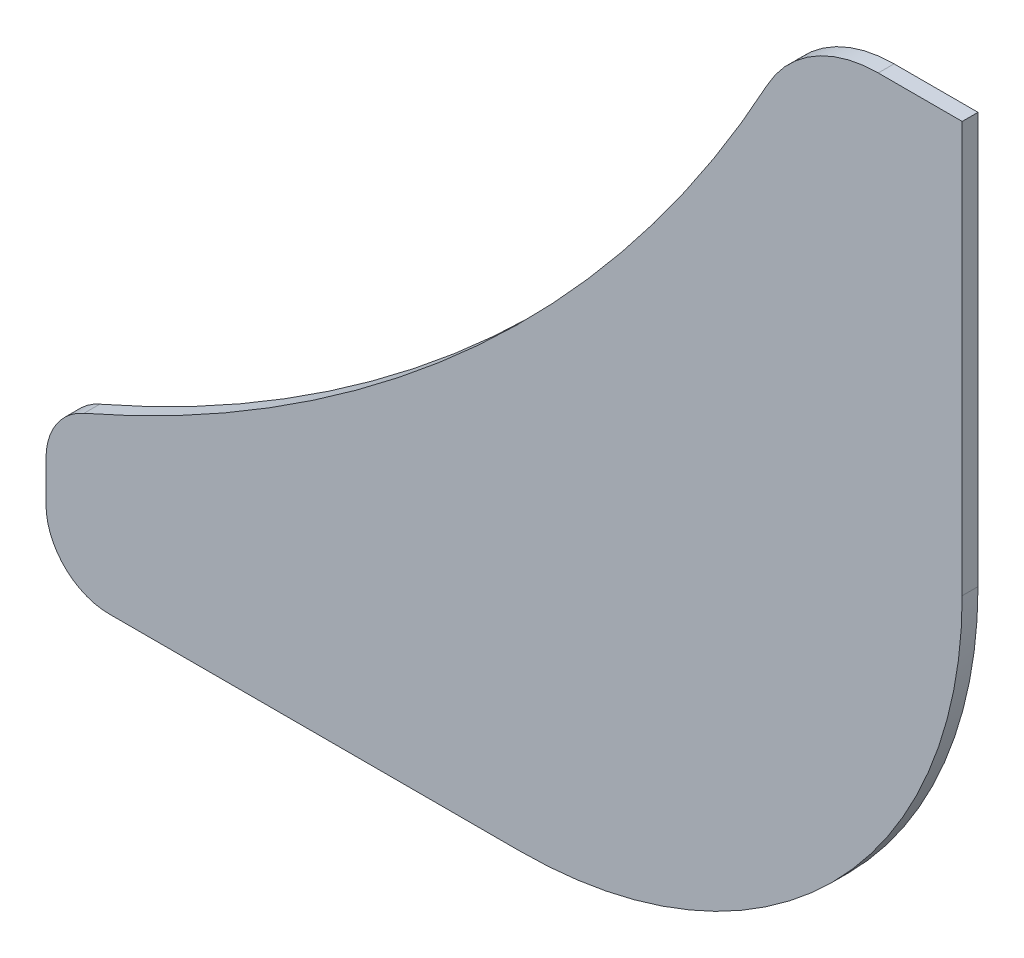
SolidWorks part; units mm, degrees
ref_plane "Front Plane" through (0, 0, 0) normal (0, 0, 1) x (1, 0, 0)
ref_plane "Top Plane" through (0, 0, 0) normal (0, 1, 0) x (1, 0, 0)
ref_plane "Right Plane" through (0, 0, 0) normal (1, 0, 0) x (0, 0, -1)
sketch "Sketch1" plane through (0, 0, 0) normal (0, 0, 1) x (1, 0, 0)
  line L15 (771.9038, 126.6023) -> (771.9038, 164.7023)
  line L17 (203.2, -228.6) -> (203.2, -261.62)
  line L20 (0, 0) -> (82.8917, 0) construction
  line L21 (0, 0) -> (0, -86.4487) construction
  line L22 (771.9038, 126.6023) -> (907.5478, 126.6023) construction
  line L25 (571.4712, -109.22) -> (571.4712, 55.88)
  line L26 (228.6, -287.02) -> (393.6712, -287.02)
  line L27 (312.4515, -206.6231) -> (466.4308, -117.7231) construction
  line L28 (451.8433, -111.2042) -> (546.0712, -26.0566) construction
  line L29 (571.4712, 55.88) -> (537.7285, 55.88)
  line L40 (361.6164, -231.6548) -> (133.988, -252.7091) construction
  line L41 (157.3315, -273.5734) -> (-70.4948, -254.7805) construction
  arc A5 (203.2, -261.62) -> (228.6, -287.02) centre (228.6, -261.62) ccw
  arc A6 (203.2, -228.6) -> (493.0974, 29.3434) centre (-9.9332, 302.8128) ccw
  arc A7 (571.4712, -109.22) -> (393.6712, -287.02) centre (393.6712, -109.22) cw
  arc A8 (537.7285, 55.88) -> (493.0974, 29.3434) centre (537.7285, 5.08) ccw
  spline S0 degree 3 poles (360.3362, -232.1476) (361.944, -231.5594) (360.2733, -231.9279) (358.8705, -232.1286) (355.491, -232.7497) (351.3118, -233.4654) (345.8288, -234.3937) (339.3319, -235.4503) (331.8137, -236.6267) (323.3898, -237.8749) (314.1481, -239.1645) (304.196, -240.4529) (293.645, -241.7102) (282.6109, -242.9031) (271.2144, -244.0118) (259.5796, -245.0173) (247.8327, -245.923) (236.1052, -246.7089) (224.5878, -247.4466) (213.3874, -247.9449) (202.6055, -248.1613) (192.2857, -248.184) (182.5214, -248.0635) (173.413, -247.8762) (165.0492, -247.6957) (157.5243, -247.5827) (150.9198, -247.5968) (145.3176, -247.8045) (140.7752, -248.2212) (137.3462, -248.9332) (134.9534, -249.8477) (133.6053, -251.5229) (134.1931, -253.5982) (136.0729, -255.3852) (139.0627, -257.3468) (143.3055, -259.3644) (148.7486, -261.4241) (155.3647, -263.3995) (163.0752, -265.2124) (171.7927, -266.7481) (181.4066, -267.9166) (191.7956, -268.6246) (202.8233, -268.8006) (214.344, -268.4024) (226.142, -267.3648) (238.0677, -265.8064) (250.0128, -263.9526) (261.9011, -261.7778) (273.6057, -259.3395) (284.9982, -256.6886) (295.9553, -253.8811) (306.362, -250.9812) (316.1121, -248.0592) (325.1026, -245.1817) (333.2481, -242.4287) (340.4703, -239.8598) (346.6777, -237.559) (351.8912, -235.562) (355.8426, -233.9905) (359.046, -232.7314) (360.3362, -232.1476) (361.944, -231.5594) (360.2733, -231.9279) knots -0.012273 -0.005484 -0.001375 0 0.001366 0.005489 0.012269 0.02165 0.033497 0.04769 0.06403 0.082338 0.102396 0.123959 0.146791 0.170641 0.19524 0.220332 0.245646 0.27091 0.295825 0.31977 0.342911 0.365083 0.386049 0.405629 0.423597 0.43978 0.453966 0.466008 0.475784 0.483219 0.48846 0.492078 0.495706 0.500976 0.508553 0.518608 0.53108 0.545907 0.56292 0.581928 0.60273 0.625094 0.648778 0.673537 0.699099 0.724814 0.750772 0.776731 0.802428 0.827555 0.851851 0.875071 0.896936 0.917223 0.935694 0.952169 0.966419 0.978318 0.987727 0.994516 0.998625 1 1.001366 1.005489 1.012269 only from (347.4667, -231.1805) to (347.4667, -231.1805) construction
  spline S1 degree 3 poles (155.9851, -273.8364) (157.6707, -273.5362) (155.9614, -273.6091) (154.545, -273.5632) (151.109, -273.588) (146.869, -273.5671) (141.3082, -273.5292) (134.7264, -273.4415) (127.1182, -273.2946) (118.6055, -273.0609) (109.2803, -272.7261) (99.2556, -272.2668) (88.6466, -271.6729) (77.573, -270.9316) (66.1571, -270.0445) (54.5244, -269.0143) (42.7988, -267.8665) (31.1129, -266.6039) (19.6424, -265.3305) (8.5257, -263.8763) (-2.1301, -262.2171) (-12.2969, -260.4475) (-21.892, -258.6332) (-30.8295, -256.8671) (-39.0349, -255.237) (-46.4259, -253.8191) (-52.9324, -252.6861) (-58.4856, -251.9178) (-63.0313, -251.5394) (-66.5319, -251.6451) (-69.0472, -252.1302) (-70.6657, -253.5459) (-70.4472, -255.6917) (-68.9062, -257.778) (-66.3025, -260.229) (-62.4745, -262.9527) (-57.4718, -265.9263) (-51.2992, -269.0205) (-44.0206, -272.1448) (-35.7023, -275.171) (-26.4373, -277.9912) (-16.3291, -280.4924) (-5.4995, -282.5807) (5.9153, -284.1891) (17.7142, -285.2159) (29.7294, -285.7521) (41.8149, -286.0007) (53.9003, -285.9233) (65.8505, -285.5546) (77.5302, -284.9222) (88.8084, -284.06) (99.5605, -283.0113) (109.6699, -281.8268) (119.0235, -280.5542) (127.5233, -279.2575) (135.0819, -277.9817) (141.5945, -276.7938) (147.0755, -275.7324) (151.2398, -274.8709) (154.6131, -274.1873) (155.9851, -273.8364) (157.6707, -273.5362) (155.9614, -273.6091) knots -0.012273 -0.005484 -0.001375 0 0.001366 0.005489 0.012269 0.02165 0.033497 0.04769 0.06403 0.082338 0.102396 0.123959 0.146791 0.170641 0.19524 0.220332 0.245646 0.27091 0.295825 0.31977 0.342911 0.365083 0.386049 0.405629 0.423597 0.43978 0.453966 0.466008 0.475784 0.483219 0.48846 0.492078 0.495706 0.500976 0.508553 0.518608 0.53108 0.545907 0.56292 0.581928 0.60273 0.625094 0.648778 0.673537 0.699099 0.724814 0.750772 0.776731 0.802428 0.827555 0.851851 0.875071 0.896936 0.917223 0.935694 0.952169 0.966419 0.978318 0.987727 0.994516 0.998625 1 1.001366 1.005489 1.012269 only from (157.3315, -273.5734) to (157.3315, -273.5734) construction
  spline S3 degree 3 poles (360.3362, -232.1476) (361.944, -231.5594) (360.2733, -231.9279) (358.8705, -232.1286) (355.491, -232.7497) (351.3118, -233.4654) (345.8288, -234.3937) (339.3319, -235.4503) (331.8137, -236.6267) (323.3898, -237.8749) (314.1481, -239.1645) (304.196, -240.4529) (293.645, -241.7102) (282.6109, -242.9031) (271.2144, -244.0118) (259.5796, -245.0173) (247.8327, -245.923) (236.1052, -246.7089) (224.5878, -247.4466) (213.3874, -247.9449) (202.6055, -248.1613) (192.2857, -248.184) (182.5214, -248.0635) (173.413, -247.8762) (165.0492, -247.6957) (157.5243, -247.5827) (150.9198, -247.5968) (145.3176, -247.8045) (140.7752, -248.2212) (137.3462, -248.9332) (134.9534, -249.8477) (133.6053, -251.5229) (134.1931, -253.5982) (136.0729, -255.3852) (139.0627, -257.3468) (143.3055, -259.3644) (148.7486, -261.4241) (155.3647, -263.3995) (163.0752, -265.2124) (171.7927, -266.7481) (181.4066, -267.9166) (191.7956, -268.6246) (202.8233, -268.8006) (214.344, -268.4024) (226.142, -267.3648) (238.0677, -265.8064) (250.0128, -263.9526) (261.9011, -261.7778) (273.6057, -259.3395) (284.9982, -256.6886) (295.9553, -253.8811) (306.362, -250.9812) (316.1121, -248.0592) (325.1026, -245.1817) (333.2481, -242.4287) (340.4703, -239.8598) (346.6777, -237.559) (351.8912, -235.562) (355.8426, -233.9905) (359.046, -232.7314) (360.3362, -232.1476) (361.944, -231.5594) (360.2733, -231.9279) knots -0.012273 -0.005484 -0.001375 0 0.001366 0.005489 0.012269 0.02165 0.033497 0.04769 0.06403 0.082338 0.102396 0.123959 0.146791 0.170641 0.19524 0.220332 0.245646 0.27091 0.295825 0.31977 0.342911 0.365083 0.386049 0.405629 0.423597 0.43978 0.453966 0.466008 0.475784 0.483219 0.48846 0.492078 0.495706 0.500976 0.508553 0.518608 0.53108 0.545907 0.56292 0.581928 0.60273 0.625094 0.648778 0.673537 0.699099 0.724814 0.750772 0.776731 0.802428 0.827555 0.851851 0.875071 0.896936 0.917223 0.935694 0.952169 0.966419 0.978318 0.987727 0.994516 0.998625 1 1.001366 1.005489 1.012269 only from (361.6164, -231.6548) to (361.6164, -231.6548) construction
  spline S8 degree 3 poles (155.9851, -273.8364) (157.6707, -273.5362) (155.9614, -273.6091) (154.545, -273.5632) (151.109, -273.588) (146.869, -273.5671) (141.3082, -273.5292) (134.7264, -273.4415) (127.1182, -273.2946) (118.6055, -273.0609) (109.2803, -272.7261) (99.2556, -272.2668) (88.6466, -271.6729) (77.573, -270.9316) (66.1571, -270.0445) (54.5244, -269.0143) (42.7988, -267.8665) (31.1129, -266.6039) (19.6424, -265.3305) (8.5257, -263.8763) (-2.1301, -262.2171) (-12.2969, -260.4475) (-21.892, -258.6332) (-30.8295, -256.8671) (-39.0349, -255.237) (-46.4259, -253.8191) (-52.9324, -252.6861) (-58.4856, -251.9178) (-63.0313, -251.5394) (-66.5319, -251.6451) (-69.0472, -252.1302) (-70.6657, -253.5459) (-70.4472, -255.6917) (-68.9062, -257.778) (-66.3025, -260.229) (-62.4745, -262.9527) (-57.4718, -265.9263) (-51.2992, -269.0205) (-44.0206, -272.1448) (-35.7023, -275.171) (-26.4373, -277.9912) (-16.3291, -280.4924) (-5.4995, -282.5807) (5.9153, -284.1891) (17.7142, -285.2159) (29.7294, -285.7521) (41.8149, -286.0007) (53.9003, -285.9233) (65.8505, -285.5546) (77.5302, -284.9222) (88.8084, -284.06) (99.5605, -283.0113) (109.6699, -281.8268) (119.0235, -280.5542) (127.5233, -279.2575) (135.0819, -277.9817) (141.5945, -276.7938) (147.0755, -275.7324) (151.2398, -274.8709) (154.6131, -274.1873) (155.9851, -273.8364) (157.6707, -273.5362) (155.9614, -273.6091) knots -0.012273 -0.005484 -0.001375 0 0.001366 0.005489 0.012269 0.02165 0.033497 0.04769 0.06403 0.082338 0.102396 0.123959 0.146791 0.170641 0.19524 0.220332 0.245646 0.27091 0.295825 0.31977 0.342911 0.365083 0.386049 0.405629 0.423597 0.43978 0.453966 0.466008 0.475784 0.483219 0.48846 0.492078 0.495706 0.500976 0.508553 0.518608 0.53108 0.545907 0.56292 0.581928 0.60273 0.625094 0.648778 0.673537 0.699099 0.724814 0.750772 0.776731 0.802428 0.827555 0.851851 0.875071 0.896936 0.917223 0.935694 0.952169 0.966419 0.978318 0.987727 0.994516 0.998625 1 1.001366 1.005489 1.012269 only from (157.3315, -273.5734) to (157.3315, -273.5734) construction
  point P9 (530.6309, 68.58)
  point P19 (571.4712, -287.02)
  point P39 (157.3315, -273.5734)
  dimension "D2" = 25.4
  dimension "D3" = 228.6
  dimension "D6" = 127
  dimension "D10" = 177.8
  dimension "D11" = 50.8
  dimension "D13" = 38.1
  dimension "D14" = 25.4
  dimension "D4" = 342.9
  dimension "D5" = 58.42
  dimension "D7" = 177.8
  dimension "D8" = 144.2667
  dimension "D9" = 203.2
extrude "Boss-Extrude1" add sketch "Sketch1" along normal blind 6.35
fillet "Fillet1" radius 25.4 1 edges at (203.2, -228.6, 3.175)
